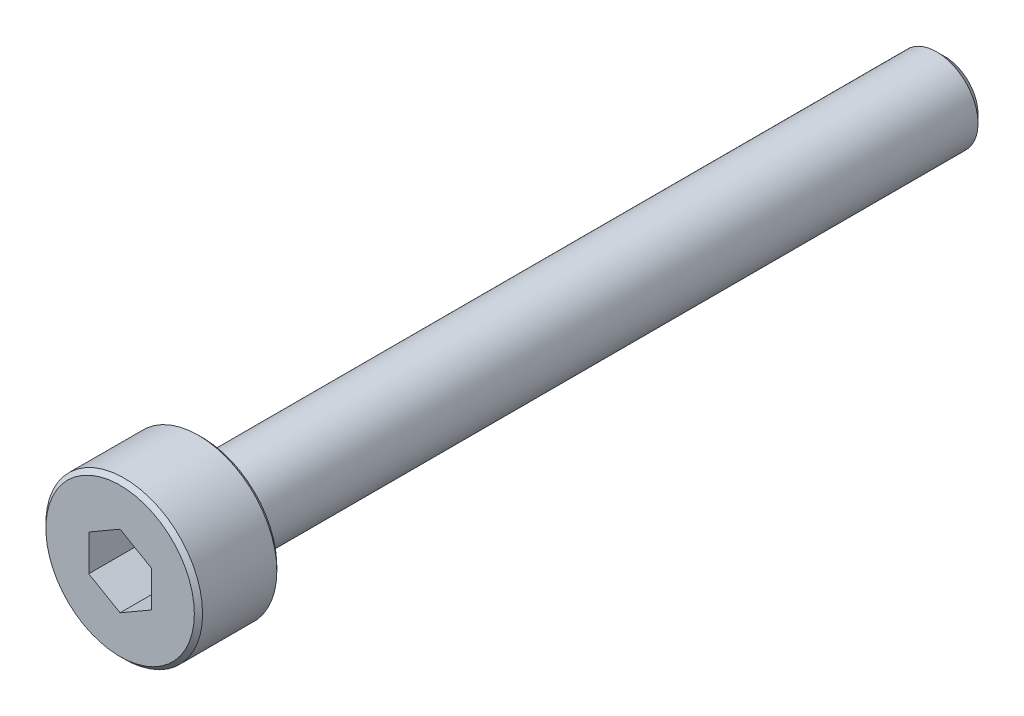
SolidWorks part; units mm, degrees
ref_plane "前视基准面" through (0, 0, 0) normal (0, 0, 1) x (1, 0, 0)
ref_plane "上视基准面" through (0, 0, 0) normal (0, 1, 0) x (1, 0, 0)
ref_plane "右视基准面" through (0, 0, 0) normal (1, 0, 0) x (0, 0, -1)
other "Configuration Table"
sketch "草图1" plane through (0, 0, 0) normal (0, 1, 0) x (1, 0, 0)
  line L0 (1.9, -10) -> (0, -10)
  line L1 (0, -10) -> (0, -12)
  line L2 (0, -12) -> (1.9, -12)
  line L3 (1.9, -12) -> (1.9, -10)
  line L4 (0, -10) -> (0, -12) construction
revolve "旋转1" add sketch "草图1" angle 360 about L4
sketch "草图2" plane through (0, 0, 10) normal (0, 0, -1) x (-1, 0, 0)
  circle A0 centre (0, 0) radius 1
extrude "凸台-拉伸1" add sketch "草图2" along normal blind 18
sketch "草图3" plane through (0, 0, 12) normal (0, 0, 1) x (1, 0, 0)
  line L0 (-0.76, -0.4388) -> (0, -0.8776)
  line L1 (0, -0.8776) -> (0.76, -0.4388)
  line L2 (0.76, -0.4388) -> (0.76, 0.4388)
  line L3 (0.76, 0.4388) -> (0, 0.8776)
  line L4 (0, 0.8776) -> (-0.76, 0.4388)
  line L5 (-0.76, 0.4388) -> (-0.76, -0.4388)
extrude "切除-拉伸1" cut sketch "草图3" against normal blind 1.5
chamfer "倒角1" distance 0.1 angle 45 2 edges at (1.9, 0, 10) (1.9, 0, 12)
chamfer "倒角2" distance 0.2 angle 45 1 edges at (-1, 0, -8)
